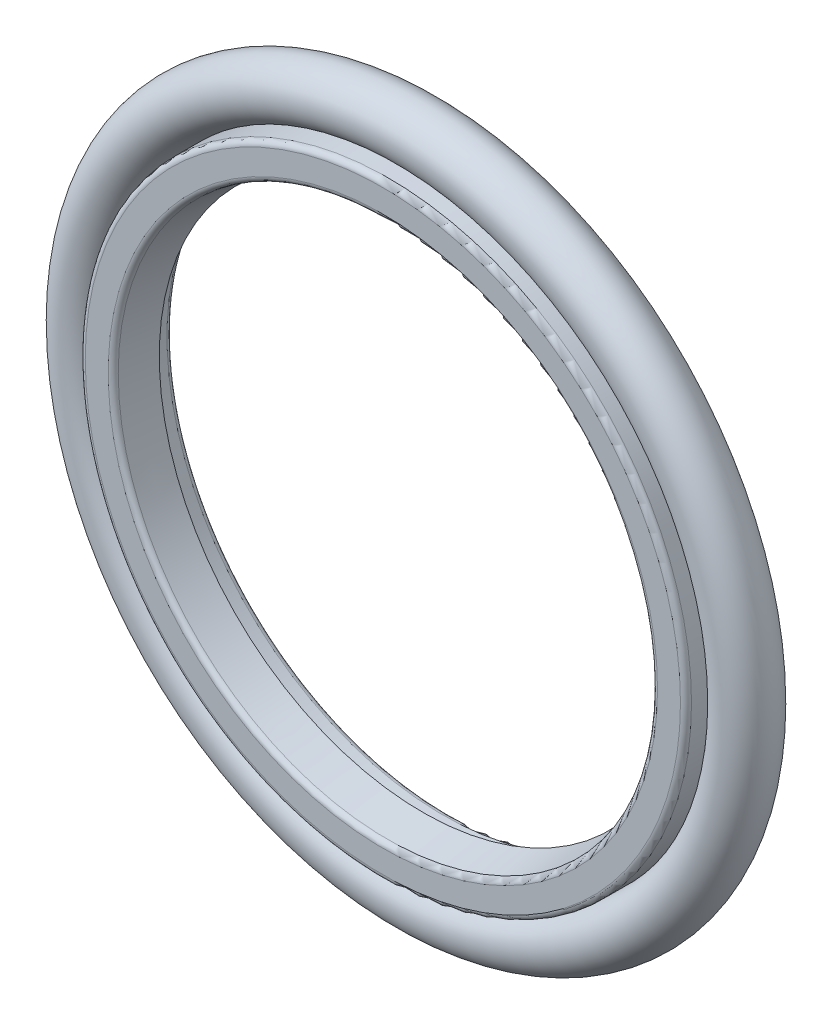
SolidWorks part; units mm, degrees
material "PTFE+NBR"
ref_plane "Front Plane" through (0, 0, 0) normal (0, 0, 1) x (1, 0, 0)
ref_plane "Top Plane" through (0, 0, 0) normal (0, 1, 0) x (1, 0, 0)
ref_plane "Right Plane" through (0, 0, 0) normal (1, 0, 0) x (0, 0, -1)
sketch "Sketch1" plane through (0, 0, 0) normal (1, 0, 0) x (0, 0, -1)
  line L0 (0, 0) -> (11.2675, 0) construction
  line L1 (0.25, 13.72) -> (2.75, 13.72)
  line L2 (0, 13.47) -> (0, 12.4318)
  line L3 (3, 13.47) -> (3, 12.77)
  line L4 (2.75, 12.52) -> (2.2, 12.52)
  line L5 (2.2, 12.52) -> (1.8, 11.92)
  line L6 (1.8, 11.92) -> (0.2089, 12.1852)
  arc A0 (0, 12.4318) -> (0.2089, 12.1852) centre (0.25, 12.4318) ccw
  arc A1 (3, 12.77) -> (2.75, 12.52) centre (2.75, 12.77) cw
  arc A2 (0.25, 13.72) -> (0, 13.47) centre (0.25, 13.47) ccw
  arc A3 (3, 13.47) -> (2.75, 13.72) centre (2.75, 13.47) ccw
  circle A4 centre (1.5, 15) radius 1.25 construction
  point P11 (0, 12.22)
  point P23 (1.5, 13.72)
  dimension "D8" = 0.25
  dimension "D12" = 32.5
  dimension "D13" = 2.5
  dimension "D14" = 0.03
  dimension "D1" = 0.8
  dimension "D2" = 1.2
  dimension "D3" = 3
  dimension "D4" = 1.5
  dimension "D5" = 27.44
  dimension "D6" = 1.8
  dimension "D7" = 1.2
  dimension "D9" = 23.84
  dimension "D10" = 24.44
  dimension "D11" = 25.04
revolve "Revolve1" add sketch "Sketch1" angle 360 about L0
sketch "Sketch2" plane through (0, 0, 0) normal (1, 0, 0) x (0, 0, -1)
  line L0 (1.5, 13.72) -> (1.5, 10.528) construction
  line L1 (2.75, 13.72) -> (0.25, 13.72) construction
  line L2 (0, 0) -> (10.3771, 0) construction
  circle A0 centre (1.5, 14.97) radius 1.25
  dimension "D1" = 2.5
  dimension "D2" = 32.44
revolve "Revolve2" add sketch "Sketch2" angle 360 about L2
